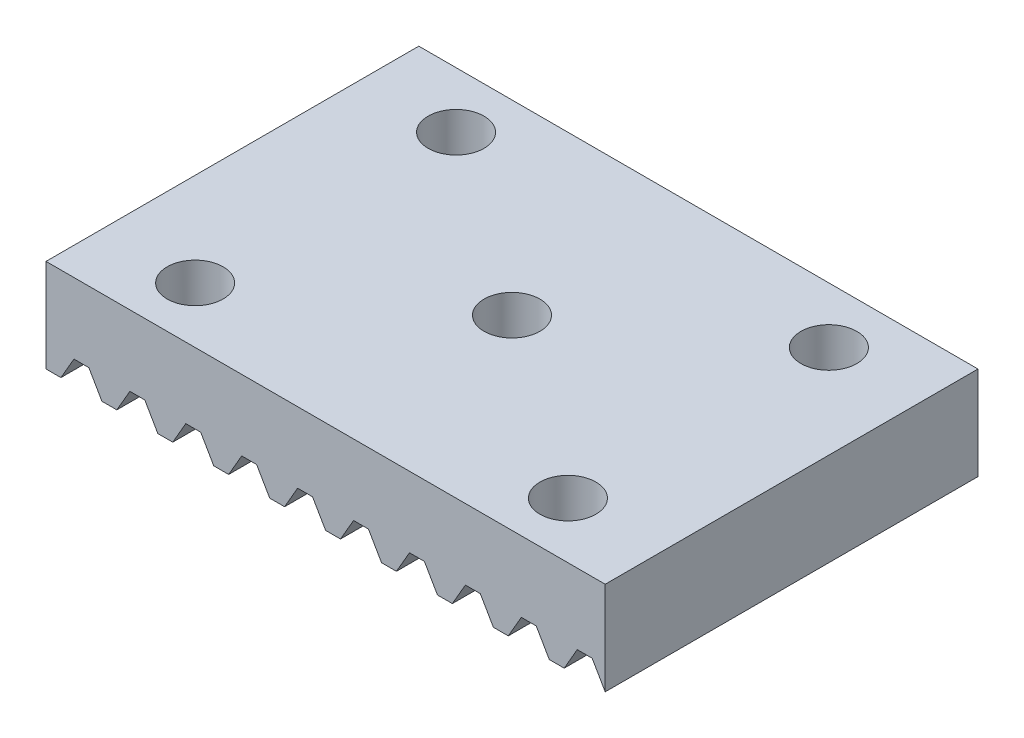
SolidWorks part; units mm, degrees
material "1060 合金"
ref_plane "前视基准面" through (0, 0, 0) normal (0, 0, 1) x (1, 0, 0)
ref_plane "上视基准面" through (0, 0, 0) normal (0, 1, 0) x (1, 0, 0)
ref_plane "右视基准面" through (0, 0, 0) normal (1, 0, 0) x (0, 0, -1)
sketch "草图1" plane through (0, 0, 0) normal (0, 1, 0) x (1, 0, 0)
  line L0 (-15, 0) -> (15, 0) construction
  line L1 (-15, 10) -> (15, 10)
  line L2 (-15, 10) -> (-15, -10)
  line L3 (-15, -10) -> (15, -10)
  line L4 (15, 10) -> (15, -10)
  line L5 (15, 4) -> (-15, 4) construction
  line L6 (15, -4) -> (-15, -4) construction
  line L7 (0, -10) -> (0, 10) construction
  circle A0 centre (-10, 7) radius 1.5
  circle A2 centre (10, 7) radius 1.5
  circle A3 centre (10, -7) radius 1.5
  circle A4 centre (-10, -7) radius 1.5
  circle A5 centre (0, 0) radius 1.5
  point P4 (0, 10)
  point P6 (15, 0)
  dimension "D4" = 3
  dimension "D7" = 3
  dimension "D1" = 20
  dimension "D2" = 30
  dimension "D3" = 8
  dimension "D5" = 3
  dimension "D6" = 5
extrude "凸台-拉伸1" add sketch "草图1" along normal blind 5
sketch "草图2" plane through (0, 0, 0) normal (0, 0, 1) x (1, 0, 0)
  line L2 (-15, 0) -> (15, 0) construction
  line L3 (-15, 0) -> (-14.2, 0)
  line L4 (-14.2, 0) -> (-13.5, 1.2124)
  line L5 (-13.5, 1.2124) -> (-12.7, 1.2124)
  line L6 (-12.7, 1.2124) -> (-12, 0)
  dimension "D1" = 120
  dimension "D2" = 120
  dimension "D3" = 0.8
  dimension "D4" = 3
extrude "切除-拉伸1" cut sketch "草图2" against normal through all both and the other way through all flip side to cut
pattern_linear "阵列(线性)1" count 10 spacing 3 along (1, 0, 0) of "切除-拉伸1"
